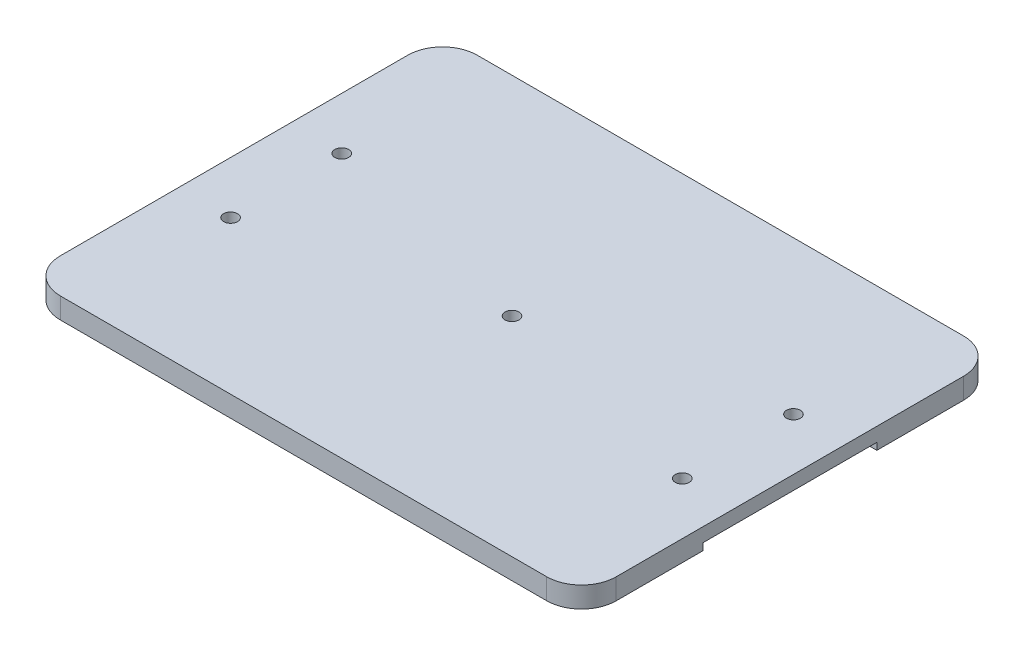
SolidWorks part; units mm, degrees
ref_plane "Front Plane" through (0, 0, 0) normal (0, 0, 1) x (1, 0, 0)
ref_plane "Top Plane" through (0, 0, 0) normal (0, 1, 0) x (1, 0, 0)
ref_plane "Right Plane" through (0, 0, 0) normal (1, 0, 0) x (0, 0, -1)
sketch "Sketch2" plane through (0, 0, 0) normal (0, 1, 0) x (1, 0, 0)
  line L1 (-59.25, 25.5) -> (20.75, 25.5)
  line L2 (-59.25, 25.5) -> (-59.25, -34.5)
  line L3 (-59.25, -34.5) -> (20.75, -34.5)
  line L4 (20.75, 25.5) -> (20.75, -34.5)
  dimension "D1" = 60
  dimension "D2" = 80
extrude "Boss-Extrude1" add sketch "Sketch2" along normal blind 3
sketch "Sketch3" plane through (0, 0, 0) normal (0, -1, 0) x (1, 0, 0)
  line L0 (-59.25, -25.5) -> (-59.25, 34.5) construction
  line L1 (-59.25, 17) -> (-44.25, 17)
  line L2 (-59.25, 17) -> (-59.25, -8)
  line L3 (-59.25, -8) -> (-44.25, -8)
  line L4 (-44.25, 17) -> (-44.25, -8)
  line L5 (-59.25, 34.5) -> (20.75, 34.5) construction
  dimension "D1" = 15
  dimension "D2" = 25
  dimension "D3" = 17.5
extrude "Cut-Extrude1" cut sketch "Sketch3" against normal blind 1 contours L2 L1 L4 L3
sketch "Sketch4" plane through (0, 1, 0) normal (0, -1, 0) x (1, 0, 0)
  line L0 (-59.25, 17) -> (-44.25, 17) construction
  line L1 (-59.25, -8) -> (-44.25, -8) construction
  line L2 (-59.25, 17) -> (-59.25, -8) construction
  circle A0 centre (-51.75, 12.5) radius 1
  circle A1 centre (-51.75, -3.5) radius 1
  point P4 (0, 0)
  dimension "D1" = 4.5
  dimension "D2" = 4.5
  dimension "D3" = 7.5
  dimension "D4" = 7.5
extrude "Cut-Extrude3" cut sketch "Sketch4" against normal blind 2
fillet "Fillet1" radius 5 4 edges at (20.75, 1.5, 34.5) (20.75, 1.5, -25.5) (-59.25, 1.5, -25.5) (-59.25, 1.5, 34.5)
sketch "Sketch5" plane through (0, 0, 0) normal (0, -1, 0) x (1, 0, 0)
  line L0 (-54.25, 34.5) -> (15.75, 34.5) construction
  line L1 (-59.25, 17) -> (-59.25, -8) construction
  circle A0 centre (-19.25, 4.5) radius 1
  dimension "D1" = 30
  dimension "D2" = 40
extrude "Cut-Extrude4" cut sketch "Sketch5" against normal blind 3
sketch "Sketch6" plane through (0, 0, 0) normal (0, 1, 0) x (1, 0, 0)
  line L0 (20.75, -29.5) -> (20.75, 20.5) construction
  line L1 (20.75, 8) -> (5.75, 8)
  line L2 (20.75, 8) -> (20.75, -17)
  line L3 (20.75, -17) -> (5.75, -17)
  line L4 (5.75, 8) -> (5.75, -17)
  line L5 (15.75, 25.5) -> (-54.25, 25.5) construction
  dimension "D1" = 15
  dimension "D2" = 25
  dimension "D3" = 17.5
extrude "Cut-Extrude6" cut sketch "Sketch6" along normal blind 1
sketch "Sketch7" plane through (0, 0, 0) normal (0, 1, 0) x (1, 0, 0)
  line L0 (20.75, 8) -> (5.75, 8) construction
  line L1 (5.75, -17) -> (20.75, -17) construction
  line L2 (5.75, 8) -> (5.75, -17) construction
  circle A0 centre (13.25, 3.5) radius 1
  circle A1 centre (13.25, -12.5) radius 1
  point P4 (0, 0)
  point P5 (0, 0)
  dimension "D1" = 2
  dimension "D2" = 4.5
  dimension "D3" = 4.5
  dimension "D4" = 7.5
  dimension "D5" = 7.5
extrude "Cut-Extrude7" cut sketch "Sketch7" along normal blind 7
